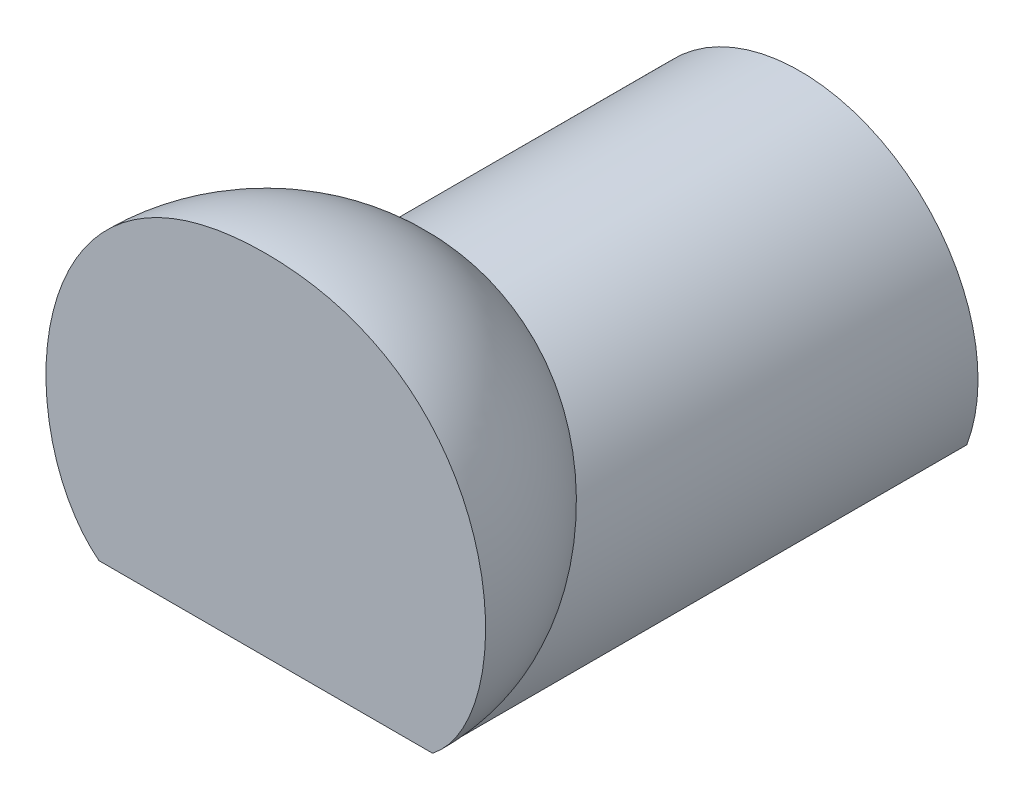
SolidWorks part; units mm, degrees
ref_plane "Front Plane" through (0, 0, 0) normal (0, 0, 1) x (1, 0, 0)
ref_plane "Top Plane" through (0, 0, 0) normal (0, 1, 0) x (1, 0, 0)
ref_plane "Right Plane" through (0, 0, 0) normal (1, 0, 0) x (0, 0, -1)
sketch "Sketch1" plane through (0, 0, 0) normal (0, 0, 1) x (1, 0, 0)
  line L0 (0, 0) -> (37.47, 0)
  arc A0 (0, 0) -> (37.47, 0) centre (18.735, 7) cw
  dimension "D1" = 20
  dimension "D2" = 7
extrude "Boss-Extrude1" add sketch "Sketch1" along normal blind 45
ref_plane "Plane1" through (0, 0, 60) normal (0, 0, 1) x (1, 0, 0)
sketch "Sketch4" plane through (0, 0, 60) normal (0, 0, 1) x (1, 0, 0)
  line L0 (18.735, 0) -> (18.735, 39.2594)
  line L1 (0, 0) -> (37.47, 0) construction
  line L2 (18.735, 0) -> (37.47, 0)
  spline S0 degree 3 poles (18.735, 39.2594) (46.1788, 39.2326) (48.0094, 8.2061) (37.47, 0) knots 0 0 0 0 1 1 1 1
  point P5 (18.735, 35.555)
  point P7 (33.2234, 26.3777)
  point P8 (34.914, 27.7376)
  point P10 (34.8484, 29.3078)
revolve "Revolve1" add sketch "Sketch4" angle 180 about L0
sketch "Sketch5" plane through (0, 0, 45) normal (0, 0, 1) x (1, 0, 0)
  line L2 (0, 0) -> (37.47, 0)
  line L3 (0, 0) -> (37.47, 0)
  arc A2 (37.47, 0) -> (0, 0) centre (18.735, 7) ccw
  arc A3 (37.47, 0) -> (0, 0) centre (18.735, 7) ccw
  dimension "D1" = 0
extrude "Boss-Extrude2" add sketch "Sketch5" along normal blind 15
